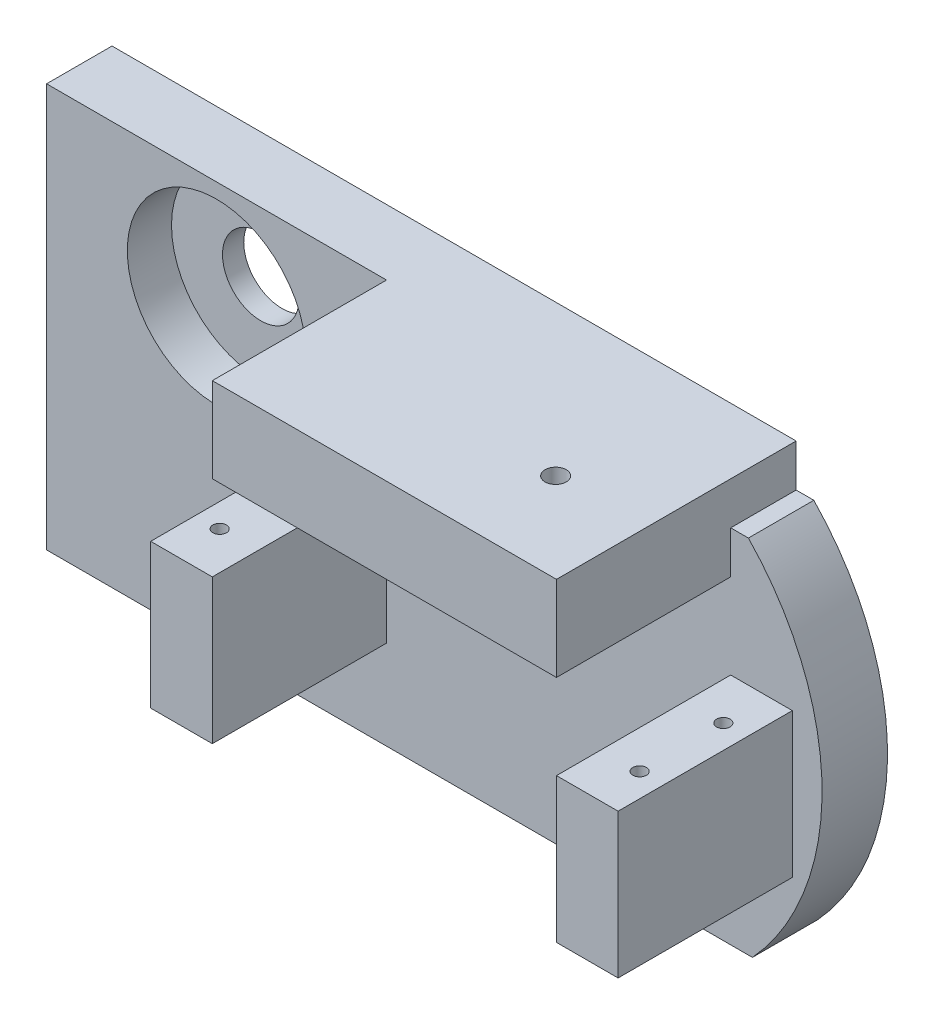
SolidWorks part; units mm, degrees
ref_plane "Plan de face" through (0, 0, 0) normal (0, 0, 1) x (1, 0, 0)
ref_plane "Plan de dessus" through (0, 0, 0) normal (0, 1, 0) x (1, 0, 0)
ref_plane "Plan de droite" through (0, 0, 0) normal (1, 0, 0) x (0, 0, -1)
sketch "Esquisse1" plane through (0, 0, 0) normal (0, 0, 1) x (1, 0, 0)
  line L1 (-27.5, 21.5) -> (27.5, 21.5)
  line L2 (-27.5, 21.5) -> (-27.5, -21.5)
  line L3 (-27.5, -21.5) -> (27.5, -21.5)
  line L4 (27.5, 21.5) -> (27.5, -21.5)
  line L5 (-27.5, 21.5) -> (27.5, -21.5) construction
  line L6 (-27.5, -21.5) -> (27.5, 21.5) construction
  point P0 (0, 0)
  dimension "D1" = 55
  dimension "D2" = 43
extrude "Boss.-Extru.1" add sketch "Esquisse1" along normal blind 27
sketch "Esquisse2" plane through (0, -21.5, 0) normal (0, -1, 0) x (1, 0, 0)
  line L0 (27.5, 27) -> (27.5, 0) construction
  line L1 (-27.5, 0) -> (27.5, 0) construction
  line L2 (-27.5, 0) -> (-27.5, 6.5) construction
  line L3 (-27.5, 6.5) -> (27.5, 6.5) construction
  line L4 (27.5, 0) -> (27.5, 6.5) construction
  line L5 (0, 0) -> (0, 33.905) construction
  line L6 (-20.25, 6.5) -> (20.25, 6.5)
  line L7 (-20.25, 6.5) -> (-20.25, 28.1766)
  line L8 (-20.25, 28.1766) -> (20.25, 28.1766)
  line L9 (20.25, 6.5) -> (20.25, 28.1766)
  dimension "D1" = 6.5
  dimension "D2" = 40.5
extrude "Enlèv. mat.-Extru.1" cut sketch "Esquisse2" against normal offset from surface (38 mm away) 5 up to face at (0, 21.5, 13.5)
sketch "Esquisse3" plane through (0, -21.5, 0) normal (0, -1, 0) x (1, 0, 0)
  line L0 (-20.25, 16.75) -> (28.5647, 16.75) construction
  line L1 (-20.25, 6.5) -> (-20.25, 27) construction
  line L2 (0, 27) -> (0, -2.6321) construction
  line L3 (-20.25, 27) -> (20.25, 27) construction
  line L4 (-20.25, 27) -> (-20.25, 6.5) construction
  circle A0 centre (-24.71, 21.675) radius 0.7
  circle A2 centre (-24.71, 11.825) radius 0.7
  circle A3 centre (24.71, 11.825) radius 0.7
  circle A4 centre (24.71, 21.675) radius 0.7
  point P9 (-24.71, 21.675)
  point P12 (-24.71, 11.825)
  point P13 (24.71, 11.825)
  point P14 (24.71, 21.675)
  dimension "D4" = 1.4
  dimension "D1" = 4.46
  dimension "D2" = 4.925
  dimension "D3" = 9.85
extrude "Enlèv. mat.-Extru.2" cut sketch "Esquisse3" against normal up to surface (43 mm away) up to face at (0, 21.5, 13.5)
sketch "Esquisse4" plane through (0, -21.5, 0) normal (0, -1, 0) x (1, 0, 0)
  line L0 (27.5, 27) -> (27.5, 0) construction
  line L1 (-27.5, 27) -> (27.5, 27)
  line L2 (-27.5, 27) -> (-27.5, 6.5)
  line L3 (-27.5, 6.5) -> (27.5, 6.5)
  line L4 (27.5, 27) -> (27.5, 6.5)
extrude "Enlèv. mat.-Extru.3" cut sketch "Esquisse4" against normal offset from surface (11 mm away) 27 up to face at (0, 16.5, 16.75)
sketch "Esquisse5" plane through (-27.5, 0, 0) normal (-1, 0, 0) x (0, 0, 1)
  line L6 (6.5, 16.5) -> (27, 16.5)
  line L7 (6.5, 16.5) -> (6.5, 6.5)
  line L8 (6.5, 6.5) -> (27, 6.5)
  line L9 (27, 16.5) -> (27, 6.5)
  line L10 (27, 21.5) -> (27, -10.5) construction
  line L11 (27, 21.5) -> (0, 21.5) construction
  line L13 (6.5, -10.5) -> (6.5, -21.5) construction
  dimension "D1" = 5
  dimension "D2" = 10
extrude "Enlèv. mat.-Extru.6" cut sketch "Esquisse5" against normal up to surface (55 mm away) up to face at (27.5, -3.5, 11.1667)
sketch "Esquisse6" plane through (0, 16.5, 0) normal (0, -1, 0) x (1, 0, 0)
  line L1 (-27.5, 27) -> (-20.25, 27)
  line L2 (-27.5, 27) -> (-27.5, 6.5)
  line L3 (-27.5, 6.5) -> (-20.25, 6.5)
  line L4 (-20.25, 27) -> (-20.25, 6.5)
  line L5 (20.25, 27) -> (27.5, 27)
  line L6 (20.25, 27) -> (20.25, 6.5)
  line L7 (20.25, 6.5) -> (27.5, 6.5)
  line L8 (27.5, 27) -> (27.5, 6.5)
extrude "Enlèv. mat.-Extru.7" cut sketch "Esquisse6" against normal up to surface (5 mm away) up to face at (24.71, 21.5, 20.975)
sketch "Esquisse7" plane through (0, 0, 0) normal (0, 0, -1) x (-1, 0, 0)
  circle A0 centre (0, 0) radius 31
  dimension "D1" = 62
extrude "Boss.-Extru.2" add sketch "Esquisse7" against normal up to surface (6.5 mm away) up to face at (0, 3.75, 6.5)
sketch "Esquisse8" plane through (0, 0, 0) normal (0, 0, -1) x (-1, 0, 0)
  circle A0 centre (0, 0) radius 31
  circle A1 centre (0, 0) radius 41
  arc A2 (22.3327, 21.5) -> (-22.3327, 21.5) centre (0, 0) ccw construction
  dimension "D1" = 62
  dimension "D2" = 82
extrude "Enlèv. mat.-Extru.8" cut sketch "Esquisse8" against normal up to surface (6.5 mm away) up to face at (0, 0, 6.5)
hole_wizard "Trou taraudé M2x0.41" positions "Esquisse3D1" profile "Esquisse9" tap size "M2x0.4" standard "Ansi Metric" end condition through all
sketch3d "Esquisse3D1"
  line L0 (-24.71, 6.5, 21.675) -> (-24.71, -10.5, 21.675) construction
  line L1 (-24.71, 6.5, 11.825) -> (-24.71, -10.5, 11.825) construction
  line L2 (24.71, 6.5, 21.675) -> (24.71, -10.5, 21.675) construction
  line L3 (24.71, 6.5, 11.825) -> (24.71, -10.5, 11.825) construction
  point P0 (-24.71, -10.5, 21.675)
  point P4 (-24.71, -10.5, 11.825)
  point P8 (24.71, -10.5, 21.675)
  point P12 (24.71, -10.5, 11.825)
sketch "Esquisse9" plane through (-24.71, -10.5, 21.675) normal (1, 0, 0) x (0, 0, -1)
  line L0 (0, 0) -> (0, 41.5)
  line L1 (0, 41.5) -> (0.8, 41.5)
  line L2 (0.8, 41.5) -> (0.8, 0)
  line L5 (0.8, 0) -> (0, 0)
  line L11 (0, -6.35) -> (0, 107.95) construction
  dimension "Diamètre du trou pour taraudage jusqu'au prochain" = 1.6
  dimension "Profondeur du trou pour taraudage jusqu'au prochain" = 41.5
cosmetic thread "Filetage de perçage1" parameters "D2"=2
cosmetic thread "Filetage de perçage2" parameters "D2"=2
cosmetic thread "Filetage de perçage3" parameters "D2"=2
cosmetic thread "Filetage de perçage4" parameters "D2"=2
sketch "Esquisse10" plane through (0, 0, 6.5) normal (0, 0, 1) x (1, 0, 0)
  circle A0 centre (0, 0) radius 10.5
  dimension "D1" = 21
extrude "Enlèv. mat.-Extru.9" cut sketch "Esquisse10" against normal offset from surface (4.5 mm away) 2 up to face at (-31, 0, 0)
sketch "Esquisse11" plane through (0, 0, 2) normal (0, 0, 1) x (1, 0, 0)
  circle A0 centre (0, 0) radius 4.5
  dimension "D1" = 9
extrude "Enlèv. mat.-Extru.10" cut sketch "Esquisse11" against normal up to surface (2 mm away) up to face at (-31, 0, 0)
sketch "Esquisse12" plane through (0, 21.5, 0) normal (0, 1, 0) x (1, 0, 0)
  line L0 (0, 0) -> (0, -31.7536) construction
  circle A0 centre (0, -15.8768) radius 9.25
  circle A1 centre (0, -15.8768) radius 1.25
  dimension "D1" = 18.5
  dimension "D2" = 2.5
extrude "Boss.-Extru.3" add sketch "Esquisse12" along normal blind 5
sketch "Esquisse13" plane through (0, 0, 6.5) normal (0, 0, 1) x (1, 0, 0)
  line L0 (-26.0408, 21.5) -> (24.0741, 21.5)
  line L1 (24.0741, 21.5) -> (24.0741, 33.5126)
  line L2 (24.0741, 33.5126) -> (-26.0408, 33.5126)
  line L3 (-26.0408, 33.5126) -> (-26.0408, 21.5)
extrude "Enlèv. mat.-Extru.11" cut sketch "Esquisse13" against normal up to surface (6.5 mm away) up to face at (4.5, 0, 0)
sketch "Esquisse14" plane through (0, 0, 0) normal (0, 0, -1) x (-1, 0, 0)
  line L0 (-22.3327, 21.5) -> (22.3327, 21.5) construction
  line L1 (-22.3327, 21.5) -> (22.3327, 21.5)
  arc A0 (-22.3327, 21.5) -> (22.3327, 21.5) centre (0, 0) ccw construction
  arc A1 (-22.3327, 21.5) -> (22.3327, 21.5) centre (0, 0) ccw
extrude "Boss.-Extru.4" add sketch "Esquisse14" along normal blind 1.2
sketch "Esquisse15" plane through (0, 0, 6.5) normal (0, 0, 1) x (1, 0, 0)
  line L0 (0, 0) -> (0, -35.7271) construction
  line L1 (26.5027, -31) -> (-26.5027, -31)
  line L2 (26.5027, -31) -> (26.5027, -21)
  line L3 (26.5027, -21) -> (-26.5027, -21)
  line L4 (-26.5027, -31) -> (-26.5027, -21)
  arc A0 (-22.3327, 21.5) -> (22.3327, 21.5) centre (0, 0) ccw construction
  dimension "D1" = 10
extrude "Enlèv. mat.-Extru.12" cut sketch "Esquisse15" against normal up to surface (7.7 mm away) up to face at (0, -4.75, -1.2)
sketch "Esquisse16" plane through (0, 0, 0) normal (0, 0, 1) x (1, 0, 0)
  circle A0 centre (0, 0) radius 4.5
extrude "Enlèv. mat.-Extru.13" cut sketch "Esquisse16" against normal up to surface (1.2 mm away) up to face at (0, 0.2967, -1.2)
sketch "Esquisse17" plane through (0, 0, 27) normal (0, 0, 1) x (1, 0, 0)
  line L0 (-20.25, 16.5) -> (20.25, 16.5) construction
  line L1 (-20.25, 21.5) -> (20.25, 21.5)
  line L2 (-20.25, 21.5) -> (-20.25, 26.5)
  line L3 (-20.25, 26.5) -> (20.25, 26.5)
  line L4 (20.25, 21.5) -> (20.25, 26.5)
  dimension "D1" = 10
extrude "Boss.-Extru.5" add sketch "Esquisse17" against normal up to vertex (42.9105 mm away)
sketch "Esquisse18" plane through (0, 26.5, 0) normal (0, 1, 0) x (1, 0, 0)
  line L0 (0, 1.2) -> (0, -28.8976) construction
  line L1 (20.25, 1.2) -> (-20.25, 1.2) construction
  line L2 (-20.25, -16.5) -> (30.3033, -16.5) construction
  line L5 (-20.25, -6.5) -> (-20.25, -27) construction
  line L6 (-20.25, -6.5) -> (-27.5, -6.5) construction
  circle A0 centre (9.65, -16.5) radius 9.25 construction
  circle A1 centre (9.65, -16.5) radius 1
  point P12 (0, -12.9)
  dimension "D1" = 29.9
  dimension "D2" = 10
extrude "Enlèv. mat.-Extru.14" cut sketch "Esquisse18" against normal up to surface (10 mm away) up to face at (0, 16.5, 16.75)
hole_wizard "Trou taraudé M3x0.51" positions "Esquisse3D2" profile "Esquisse19" tap size "M3x0.5" standard "Ansi Metric" end condition through all
sketch3d "Esquisse3D2"
  line L0 (9.65, 16.5, 16.5) -> (9.65, 26.5, 16.5) construction
  point P0 (9.65, 26.5, 16.5)
sketch "Esquisse19" plane through (9.65, 26.5, 16.5) normal (1, 0, 0) x (0, 0, 1)
  line L0 (0, 0) -> (0, 47.5)
  line L1 (0, 47.5) -> (1.25, 47.5)
  line L2 (1.25, 47.5) -> (1.25, 0)
  line L5 (1.25, 0) -> (0, 0)
  line L11 (0, -6.35) -> (0, 107.95) construction
  dimension "Diamètre du trou pour taraudage jusqu'au prochain" = 2.5
  dimension "Profondeur du trou pour taraudage jusqu'au prochain" = 47.5
cosmetic thread "Filetage de perçage5" parameters "D2"=3
sketch "Esquisse22" plane through (0, 0, -1.2) normal (0, 0, -1) x (-1, 0, 0)
  line L0 (-4.3965, 26.5) -> (-4.3965, 31.5) construction
  line L1 (-20.25, 26.5) -> (20.25, 26.5) construction
  line L2 (-8.6455, 31.5) -> (47.4898, 31.5) construction
  line L3 (0, 31.5) -> (0, -22.3061) construction
  line L4 (8.6772, 14.25) -> (45.8556, 14.25) construction
  line L5 (22.8035, -21) -> (-22.8035, -21) construction
  line L6 (20.25, 26.5) -> (60.25, 26.5)
  line L7 (20.25, 26.5) -> (20.25, 2)
  line L9 (60.25, 26.5) -> (60.25, 2)
  line L13 (20.25, 2) -> (20.25, -21)
  line L14 (20.25, -21) -> (60.25, -21)
  line L15 (20.25, 26.5) -> (20.25, 21.5) construction
  line L16 (60.25, 2) -> (60.25, -21)
  circle A0 centre (40.25, 14.25) radius 10.5 construction
  circle A1 centre (40.25, 14.25) radius 4.5
  dimension "D1" = 5
  dimension "D2" = 17.25
  dimension "D3" = 35.25
  dimension "D5" = 40
  dimension "D4" = 20
extrude "Boss.-Extru.6" add sketch "Esquisse22" against normal up to surface (7.7 mm away) up to face at (10.5, 0, 6.5)
sketch "Esquisse23" plane through (0, 0, 6.5) normal (0, 0, 1) x (1, 0, 0)
  circle A0 centre (-40.25, 14.25) radius 10.5
extrude "Enlèv. mat.-Extru.15" cut sketch "Esquisse23" against normal offset from surface (5.2 mm away) 2.5 up to face at (-4.4056, 9.0156, -1.2)
sketch "Esquisse24" plane through (0, 0, -1.2) normal (0, 0, -1) x (-1, 0, 0)
  circle A0 centre (0, 0) radius 12.8852
extrude "Boss.-Extru.7" add sketch "Esquisse24" against normal up to surface (7.7 mm away) up to face at (-29.75, 14.25, 6.5)
equation "\"1c\"=0.00309185"
equation "\"D2@Esquisse8\"=\"D1@Esquisse8\"+2cm"
equation "\"6c\"=0.04"
equation "\"D4@Esquisse22\"=\"D5@Esquisse22\"-2cm"
